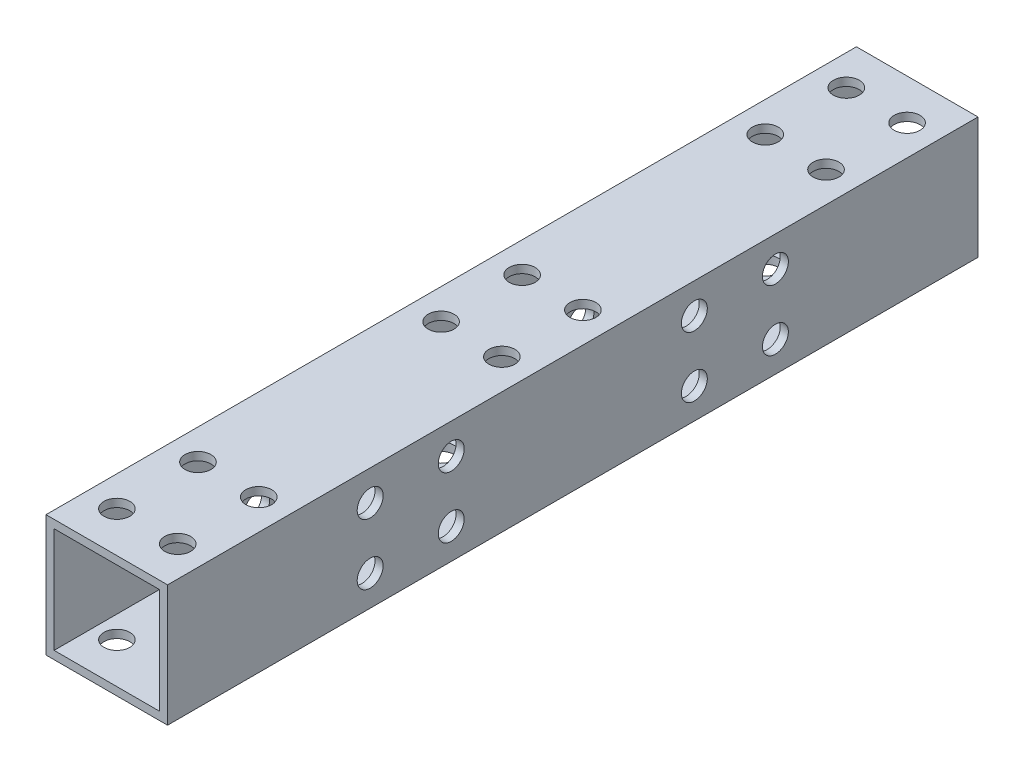
SolidWorks part; units mm, degrees
ref_plane "前视基准面" through (0, 0, 0) normal (0, 0, 1) x (1, 0, 0)
ref_plane "上视基准面" through (0, 0, 0) normal (0, 1, 0) x (1, 0, 0)
ref_plane "右视基准面" through (0, 0, 0) normal (1, 0, 0) x (0, 0, -1)
other "Configuration Table"
sketch "草图1" plane through (0, 0, 0) normal (0, 0, 1) x (1, 0, 0)
  line L1 (0, 0) -> (15, 0)
  line L2 (0, 0) -> (0, -15)
  line L3 (0, -15) -> (15, -15)
  line L4 (15, 0) -> (15, -15)
  dimension "D1" = 15
  dimension "D2" = 15
extrude "拉伸-薄壁1" add sketch "草图1" along normal blind 100 thin
sketch "草图2" plane through (15, 0, 0) normal (1, 0, 0) x (0, 0, -1)
  line L1 (-100, 0) -> (0, 0) construction
  line L2 (-100, -15) -> (0, -15) construction
  line L3 (-70, 0) -> (-70, -15) construction
  line L4 (-100, -15) -> (-100, 0) construction
  line L5 (-100, -7.5) -> (-70, -7.5) construction
  line L6 (-30, 0) -> (-30, -15) construction
  line L7 (0, -7.5) -> (-30, -7.5) construction
  line L8 (0, -15) -> (0, 0) construction
  line L9 (-30, -7.5) -> (-70, -7.5) construction
  circle A0 centre (-75, -3.75) radius 1.6
  circle A1 centre (-75, -11.25) radius 1.6
  circle A2 centre (-65, -11.25) radius 1.6
  circle A3 centre (-65, -3.75) radius 1.6
  circle A8 centre (-25, -3.75) radius 1.6
  circle A9 centre (-25, -11.25) radius 1.6
  circle A10 centre (-35, -11.25) radius 1.6
  circle A11 centre (-35, -3.75) radius 1.6
  point P0 (-29.205, -7.5)
  dimension "D2" = 3.2
  dimension "D6" = 3.2
  dimension "D1" = 30
  dimension "D3" = 5
  dimension "D4" = 3.75
  dimension "D5" = 30
  dimension "D7" = 3.75
  dimension "D8" = 5
extrude "切除-拉伸1" cut sketch "草图2" against normal through all
sketch "草图3" plane through (0, 0, 0) normal (0, 1, 0) x (1, 0, 0)
  line L0 (7.5, 0) -> (7.5, -100) construction
  line L1 (15, 0) -> (0, 0) construction
  line L2 (15, -100) -> (0, -100) construction
  line L3 (15, -50) -> (0, -50) construction
  line L4 (15, -100) -> (15, 0) construction
  line L5 (0, -100) -> (0, 0) construction
  line L6 (0, -10) -> (15, -10) construction
  line L7 (0, -90) -> (15, -90) construction
  circle A0 centre (3.75, -5) radius 1.6
  circle A1 centre (11.25, -5) radius 1.6
  circle A2 centre (11.25, -15) radius 1.6
  circle A3 centre (3.75, -15) radius 1.6
  circle A16 centre (3.75, -45) radius 1.6
  circle A17 centre (11.25, -45) radius 1.6
  circle A18 centre (11.25, -55) radius 1.6
  circle A19 centre (3.75, -55) radius 1.6
  circle A28 centre (3.75, -85) radius 1.6
  circle A29 centre (11.25, -85) radius 1.6
  circle A30 centre (11.25, -95) radius 1.6
  circle A31 centre (3.75, -95) radius 1.6
  dimension "D1" = 3.2
  dimension "D7" = 3.2
  dimension "D2" = 3.75
  dimension "D3" = 10
  dimension "D4" = 5
  dimension "D8" = 5
  dimension "D9" = 3.75
extrude "切除-拉伸2" cut sketch "草图3" against normal through all
